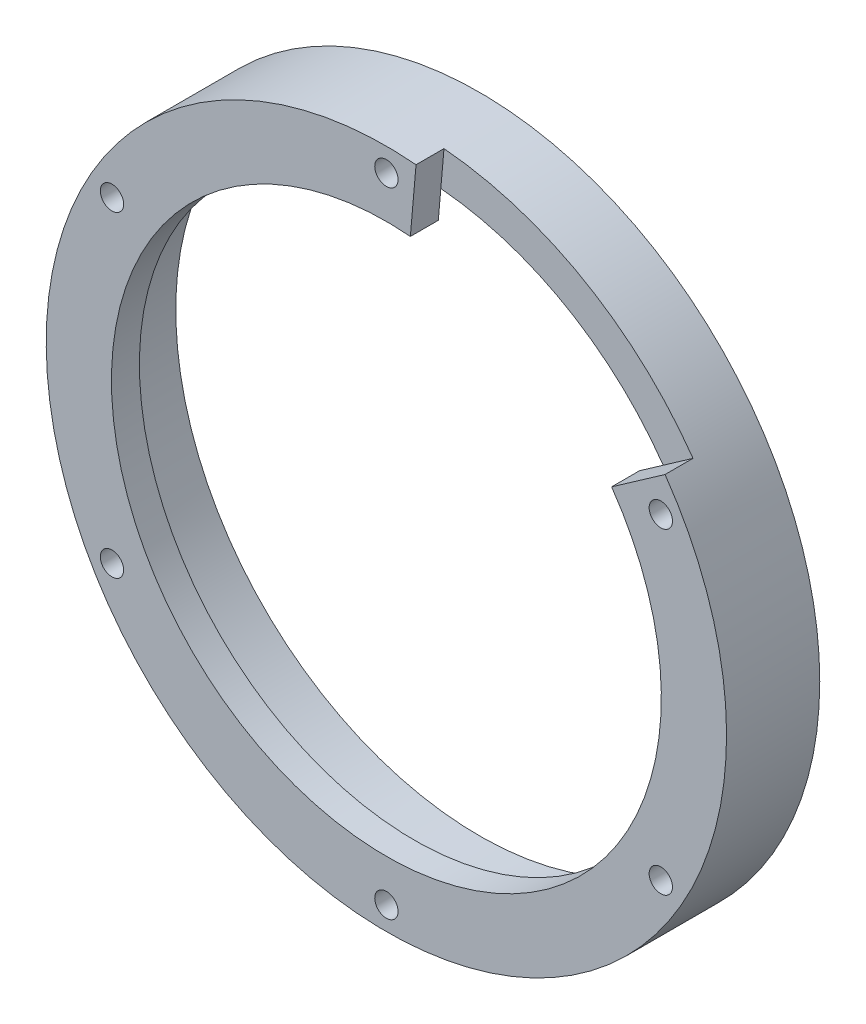
SolidWorks part; units mm, degrees
ref_plane "前视基准面" through (0, 0, 0) normal (0, 0, 1) x (1, 0, 0)
ref_plane "上视基准面" through (0, 0, 0) normal (0, 1, 0) x (1, 0, 0)
ref_plane "右视基准面" through (0, 0, 0) normal (1, 0, 0) x (0, 0, -1)
other "Configuration Table"
sketch "草图1" plane through (0, 0, 0) normal (0, 0, 1) x (1, 0, 0)
  circle A0 centre (0, 0) radius 32.6
  circle A1 centre (0, 0) radius 36.5
  dimension "D1" = 65.2
  dimension "D2" = 73
extrude "凸台-拉伸1" add sketch "草图1" along normal mid plane 7
sketch "草图2" plane through (0, 0, 3.5) normal (0, 0, 1) x (1, 0, 0)
  circle A0 centre (0, 0) radius 36.5 construction
  circle A1 centre (0, 0) radius 36.5
  circle A2 centre (0, 0) radius 29.5
  dimension "D1" = 59
extrude "凸台-拉伸2" add sketch "草图2" along normal blind 3
sketch "草图3" plane through (0, 0, -3.5) normal (0, 0, -1) x (-1, 0, 0)
  circle A0 centre (0, 34) radius 1.25
  circle A1 centre (29.4449, 17) radius 1.25
  circle A2 centre (29.4449, -17) radius 1.25
  circle A3 centre (0, -34) radius 1.25
  circle A4 centre (-29.4449, -17) radius 1.25
  circle A5 centre (-29.4449, 17) radius 1.25
  point P16 (0, 0)
  dimension "D1" = 2.5
  dimension "D2" = 34
  dimension "D3" = 6
extrude "切除-拉伸1" cut sketch "草图3" against normal blind 20
sketch "草图4" plane through (0, 0, 6.5) normal (0, 0, 1) x (1, 0, 0)
  line L0 (3.1812, 36.3611) -> (0, 0)
  line L1 (0, 0) -> (29.899, 20.9355)
  line L2 (0, 36.5) -> (0, 0) construction
  circle A0 centre (0, 0) radius 36.5 construction
  circle A1 centre (0, 0) radius 29.5 construction
  circle A2 centre (0, 0) radius 29.5
  circle A3 centre (0, 0) radius 36.5
  circle M10 centre (0, 0) radius 36.5
  circle M11 centre (0, 0) radius 29.5
  dimension "D1" = 50
  dimension "D2" = 5
extrude "切除-拉伸2" cut sketch "草图4" against normal blind 3 contours L1 L0 M11 M10
